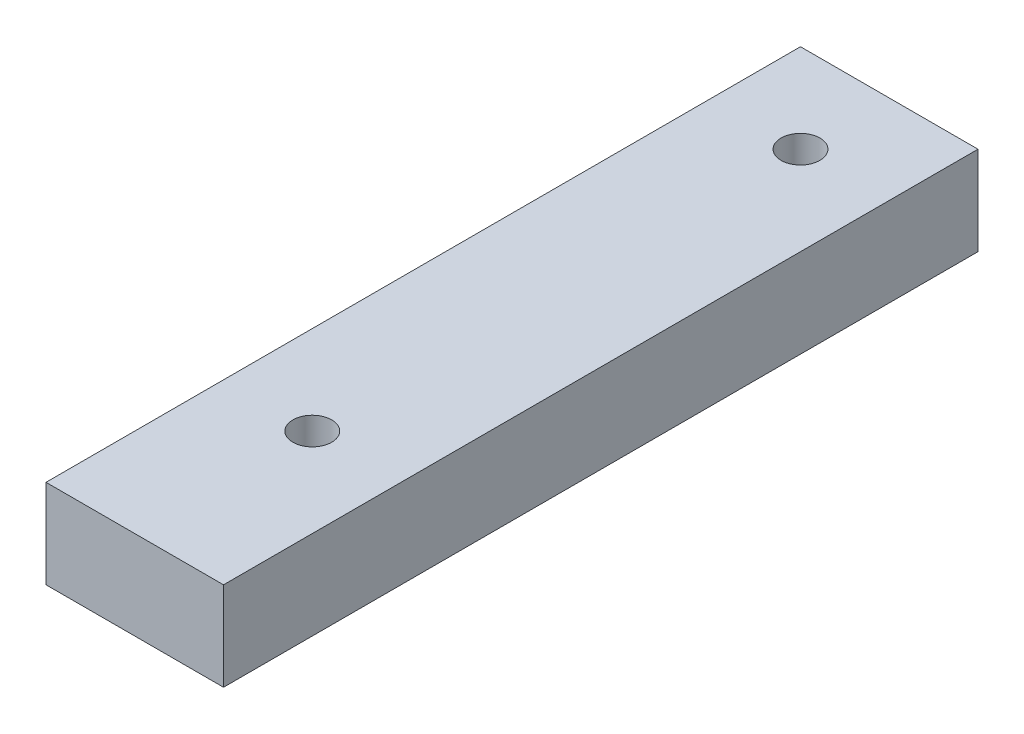
SolidWorks part; units mm, degrees
material "Beech"
ref_plane "Front Plane" through (0, 0, 0) normal (0, 0, 1) x (1, 0, 0)
ref_plane "Top Plane" through (0, 0, 0) normal (0, 1, 0) x (1, 0, 0)
ref_plane "Right Plane" through (0, 0, 0) normal (1, 0, 0) x (0, 0, -1)
sketch "Sketch1" plane through (0, 0, 0) normal (0, 1, 0) x (1, 0, 0)
  line L1 (0, 0) -> (304.8, 0)
  line L2 (0, 0) -> (0, 304.8)
  line L3 (0, 304.8) -> (304.8, 304.8)
  line L4 (304.8, 0) -> (304.8, 304.8)
  dimension "D1" = 304.8
  dimension "D2" = 304.8
extrude "Boss-Extrude1" add sketch "Sketch1" along normal blind 6.35
sketch "Sketch2" plane through (0, 6.35, 0) normal (0, 1, 0) x (1, 0, 0)
  line L1 (304.8, 304.8) -> (0, 304.8) construction
  line L2 (12.7, 304.8) -> (12.7, 250.825)
  line L3 (12.7, 250.825) -> (0, 250.825)
  line L4 (0, 304.8) -> (0, 0) construction
  line L6 (0, 250.825) -> (0, 0)
  line L7 (0, 0) -> (304.8, 0)
  line L8 (304.8, 0) -> (304.8, 304.8)
  line L9 (304.8, 304.8) -> (12.7, 304.8)
  dimension "D1" = 12.7
  dimension "D2" = 53.975
extrude "Cut-Extrude2" cut sketch "Sketch2" against normal blind 6.35 contours L3 L6 L7 L8 L9 L2
sketch "Sketch3" plane through (0, 6.35, 0) normal (0, 1, 0) x (1, 0, 0)
  line L0 (0, 304.8) -> (0, 250.825) construction
  line L1 (12.7, 304.8) -> (0, 304.8) construction
  line L2 (12.7, 250.825) -> (0, 250.825) construction
  circle A0 centre (6.35, 263.525) radius 1.3891
  circle A1 centre (6.35, 298.45) radius 1.3891
  dimension "D1" = 2.7781
  dimension "D2" = 2.7781
  dimension "D3" = 6.35
  dimension "D4" = 6.35
  dimension "D5" = 6.35
  dimension "D6" = 12.7
extrude "Cut-Extrude3" cut sketch "Sketch3" against normal through all
